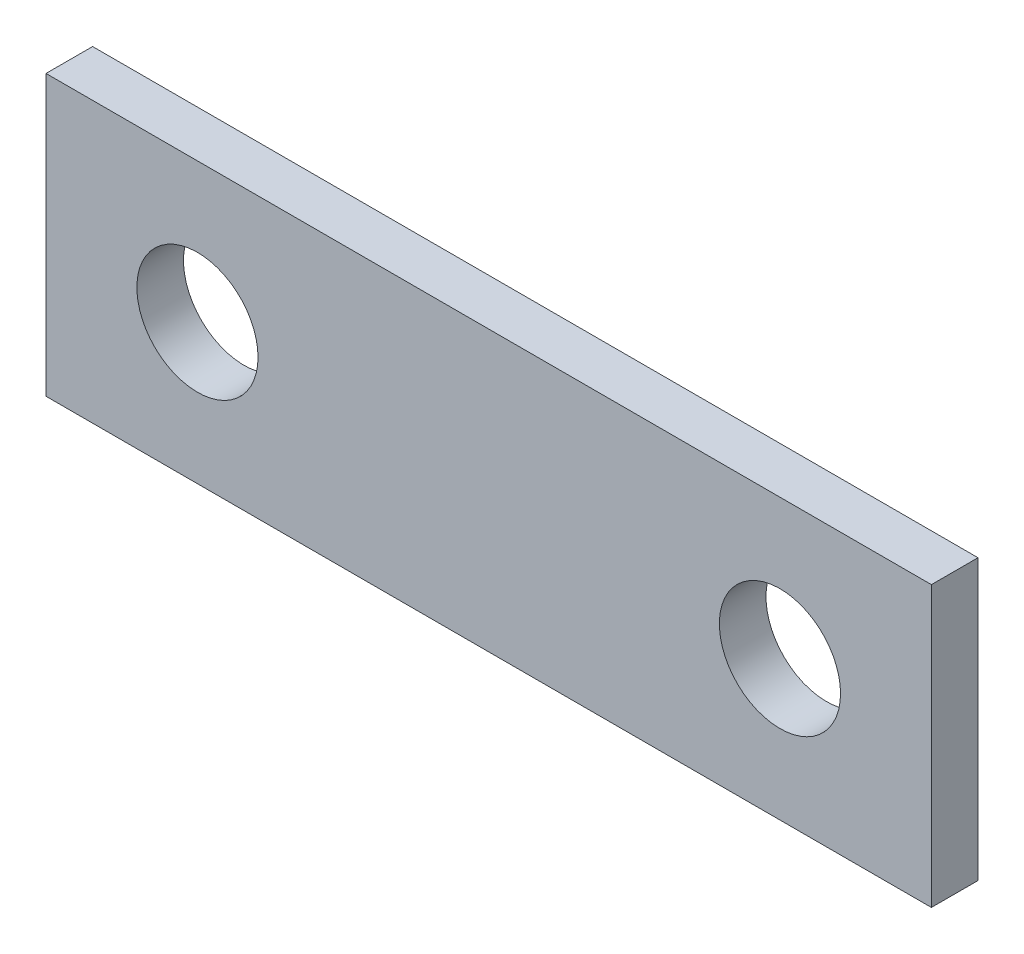
SolidWorks part; units mm, degrees
ref_plane "Front" through (0, 0, 0) normal (0, 0, 1) x (1, 0, 0)
ref_plane "Top" through (0, 0, 0) normal (0, 1, 0) x (1, 0, 0)
ref_plane "Right" through (0, 0, 0) normal (1, 0, 0) x (0, 0, -1)
sketch "草图1" plane through (0, 0, 0) normal (0, 0, 1) x (1, 0, 0)
  line L1 (-19, -6) -> (19, -6)
  line L2 (-19, -6) -> (-19, 6)
  line L3 (-19, 6) -> (19, 6)
  line L4 (19, -6) -> (19, 6)
  line L5 (-19, -6) -> (19, 6) construction
  line L6 (-19, 6) -> (19, -6) construction
  circle A0 centre (12.5, 0) radius 2.6
  circle A1 centre (-12.5, 0) radius 2.6
  point P0 (0, 0)
  dimension "D1" = 38
  dimension "D2" = 12
extrude "凸台-拉伸1" add sketch "草图1" along normal blind 2
